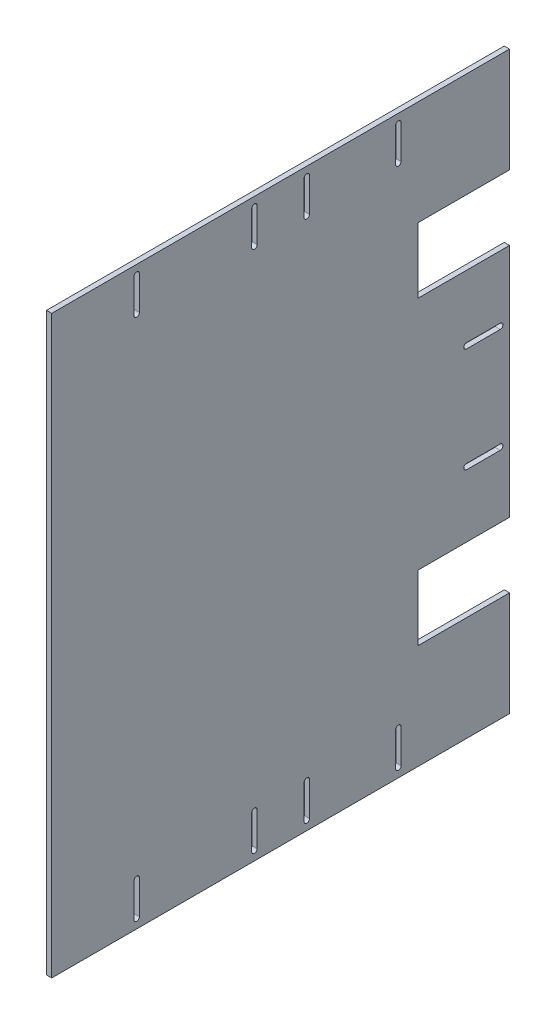
SolidWorks part; units mm, degrees
ref_plane "Front Plane" through (0, 0, 0) normal (1, 0, 0) x (0, 1, 0)
ref_plane "Top Plane" through (0, 0, 0) normal (0, 0, 1) x (0, 1, 0)
ref_plane "Right Plane" through (0, 0, 0) normal (0, 1, 0) x (-1, 0, 0)
sketch "Sketch1" plane through (0, 0, 0) normal (1, 0, 0) x (0, 1, 0)
  line L0 (0, 0) -> (440, 0)
  line L1 (440, 0) -> (440, 350)
  line L2 (440, 350) -> (0, 350)
  line L3 (0, 350) -> (0, 0)
  line L4 (220, 0) -> (220, 55.2182) construction
  line L5 (80, 0) -> (130, 0)
  line L6 (80, 0) -> (80, 70)
  line L7 (80, 70) -> (130, 70)
  line L8 (130, 0) -> (130, 70)
  line L9 (360, 0) -> (360, 70)
  line L10 (360, 70) -> (310, 70)
  line L11 (310, 0) -> (310, 70)
  line L12 (180, 32.9) -> (180, 7.1) construction
  line L13 (177.9, 32.9) -> (177.9, 7.1)
  line L14 (182.1, 32.9) -> (182.1, 7.1)
  line L15 (260, 32.9) -> (260, 7.1) construction
  line L16 (262.1, 32.9) -> (262.1, 7.1)
  line L17 (257.9, 32.9) -> (257.9, 7.1)
  line L18 (32.9, 85) -> (7.1, 85) construction
  line L19 (32.9, 87.1) -> (7.1, 87.1)
  line L20 (32.9, 82.9) -> (7.1, 82.9)
  line L21 (0, 120) -> (100.2337, 120) construction
  line L22 (32.9, 155) -> (7.1, 155) construction
  line L23 (32.9, 152.9) -> (7.1, 152.9)
  line L24 (32.9, 157.1) -> (7.1, 157.1)
  line L25 (407.1, 85) -> (432.9, 85) construction
  line L26 (407.1, 87.1) -> (432.9, 87.1)
  line L27 (407.1, 82.9) -> (432.9, 82.9)
  line L28 (407.1, 155) -> (432.9, 155) construction
  line L29 (407.1, 152.9) -> (432.9, 152.9)
  line L30 (407.1, 157.1) -> (432.9, 157.1)
  line L31 (32.9, 285) -> (7.1, 285) construction
  line L32 (32.9, 282.9) -> (7.1, 282.9)
  line L33 (32.9, 287.1) -> (7.1, 287.1)
  line L34 (0, 240) -> (66.7278, 240) construction
  line L35 (32.9, 195) -> (7.1, 195) construction
  line L36 (32.9, 197.1) -> (7.1, 197.1)
  line L37 (32.9, 192.9) -> (7.1, 192.9)
  line L38 (407.1, 195) -> (432.9, 195) construction
  line L39 (407.1, 197.1) -> (432.9, 197.1)
  line L40 (407.1, 192.9) -> (432.9, 192.9)
  line L41 (407.1, 285) -> (432.9, 285) construction
  line L42 (407.1, 282.9) -> (432.9, 282.9)
  line L43 (407.1, 287.1) -> (432.9, 287.1)
  arc A0 (177.9, 32.9) -> (182.1, 32.9) centre (180, 32.9) cw
  arc A1 (182.1, 7.1) -> (177.9, 7.1) centre (180, 7.1) cw
  arc A2 (262.1, 32.9) -> (257.9, 32.9) centre (260, 32.9) ccw
  arc A3 (257.9, 7.1) -> (262.1, 7.1) centre (260, 7.1) ccw
  arc A4 (32.9, 87.1) -> (32.9, 82.9) centre (32.9, 85) cw
  arc A5 (7.1, 82.9) -> (7.1, 87.1) centre (7.1, 85) cw
  arc A6 (32.9, 152.9) -> (32.9, 157.1) centre (32.9, 155) ccw
  arc A7 (7.1, 157.1) -> (7.1, 152.9) centre (7.1, 155) ccw
  arc A8 (407.1, 87.1) -> (407.1, 82.9) centre (407.1, 85) ccw
  arc A9 (432.9, 82.9) -> (432.9, 87.1) centre (432.9, 85) ccw
  arc A10 (407.1, 152.9) -> (407.1, 157.1) centre (407.1, 155) cw
  arc A11 (432.9, 157.1) -> (432.9, 152.9) centre (432.9, 155) cw
  arc A12 (32.9, 282.9) -> (32.9, 287.1) centre (32.9, 285) ccw
  arc A13 (7.1, 287.1) -> (7.1, 282.9) centre (7.1, 285) ccw
  arc A14 (32.9, 197.1) -> (32.9, 192.9) centre (32.9, 195) cw
  arc A15 (7.1, 192.9) -> (7.1, 197.1) centre (7.1, 195) cw
  arc A16 (407.1, 197.1) -> (407.1, 192.9) centre (407.1, 195) ccw
  arc A17 (432.9, 192.9) -> (432.9, 197.1) centre (432.9, 195) ccw
  arc A18 (407.1, 282.9) -> (407.1, 287.1) centre (407.1, 285) cw
  arc A19 (432.9, 287.1) -> (432.9, 282.9) centre (432.9, 285) cw
  point P3 (220, 350)
  point P6 (220, 0)
  point P19 (180, 20)
  point P27 (260, 20)
  point P35 (20, 85)
  point P42 (20, 155)
  point P50 (420, 85)
  point P57 (420, 155)
  point P64 (20, 285)
  point P69 (5, 285)
  point P73 (20, 195)
  point P80 (420, 195)
  point P87 (420, 285)
  dimension "D6" = 30
  dimension "D8" = 5
  dimension "D1" = 440
  dimension "D2" = 350
  dimension "D3" = 70
  dimension "D4" = 50
  dimension "D5" = 90
  dimension "D7" = 4.2
  dimension "D9" = 80
  dimension "D10" = 5
  dimension "D11" = 85
  dimension "D12" = 70
  dimension "D13" = 5
  dimension "D14" = 65
  dimension "D15" = 90
extrude "Boss-Extrude1" add sketch "Sketch1" along normal blind 4
